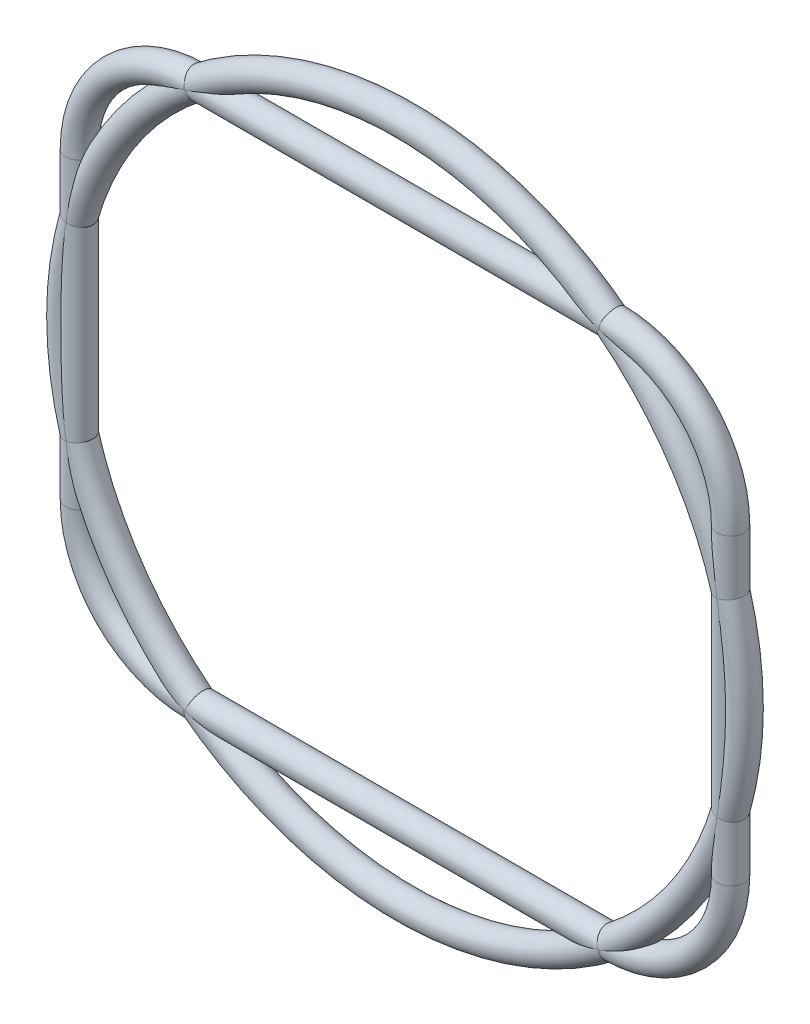
SolidWorks part; units mm, degrees
ref_plane "Front Plane" through (0, 0, 0) normal (0, 0, 1) x (1, 0, 0)
ref_plane "Top Plane" through (0, 0, 0) normal (0, 1, 0) x (1, 0, 0)
ref_plane "Right Plane" through (0, 0, 0) normal (1, 0, 0) x (0, 0, -1)
sketch "Sketch1" plane through (0, 0, 0) normal (1, 0, 0) x (0, 0, -1)
  line L0 (0, 0) -> (34.2132, 0) construction
  circle A0 centre (0, 37.5) radius 1.5
  dimension "D1" = 72
  dimension "D2" = 3
revolve "Revolve1" add sketch "Sketch1" angle 360 about L0
sketch "Sketch2" plane through (0, 0, 0) normal (0, 0, 1) x (1, 0, 0)
  line L0 (0, 0) -> (0, 20.7836) construction
  line L1 (-23, 29.75) -> (23, 29.75)
  line L2 (-36, 16.75) -> (-36, -16.75)
  line L3 (-23, -29.75) -> (23, -29.75)
  line L4 (36, 16.75) -> (36, -16.75)
  line L5 (0, 0) -> (32.1154, 0) construction
  arc A0 (-36, -16.75) -> (-23, -29.75) centre (-23, -16.75) ccw
  arc A1 (23, -29.75) -> (36, -16.75) centre (23, -16.75) ccw
  arc A2 (23, 29.75) -> (36, 16.75) centre (23, 16.75) cw
  arc A3 (-23, 29.75) -> (-36, 16.75) centre (-23, 16.75) ccw
  dimension "D3" = 13
  dimension "D1" = 59.5
  dimension "D2" = 72
sketch "Sketch3" plane through (0, 0, 0) normal (1, 0, 0) x (0, 0, -1)
  circle A0 centre (0, 29.75) radius 1.5
  dimension "D1" = 3
sweep "Sweep1" add profiles "Sketch3" path "Sketch2"
